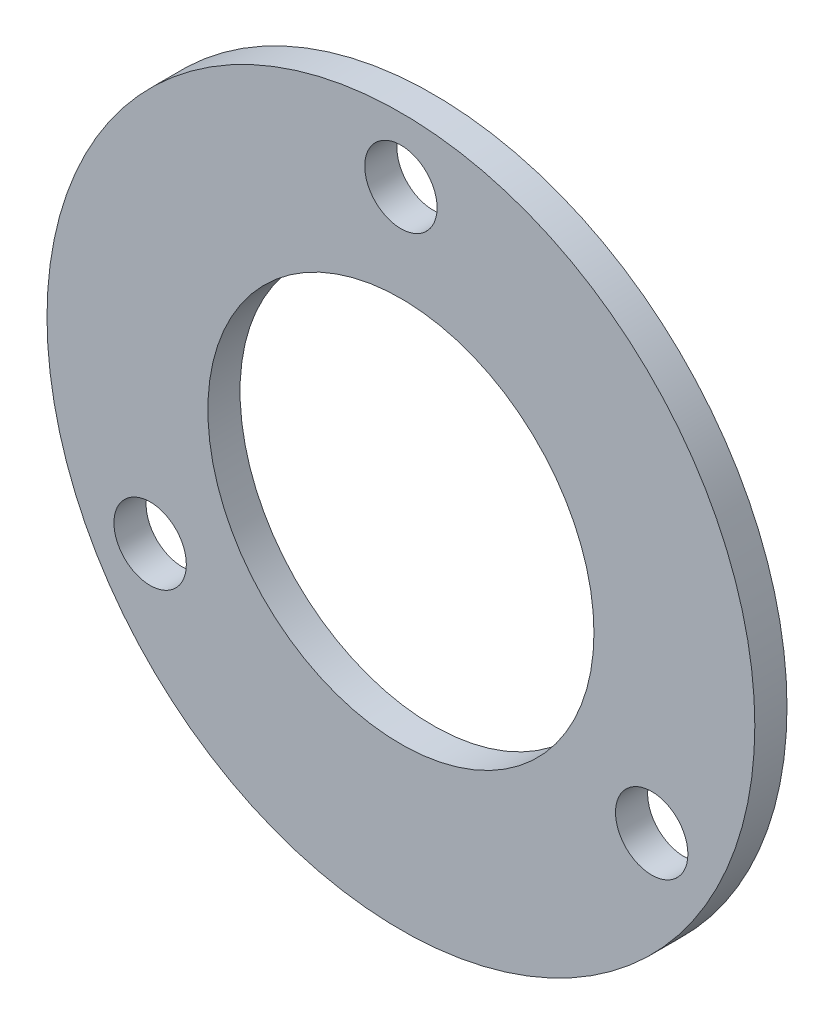
SolidWorks part; units mm, degrees
ref_plane "Front Plane" through (0, 0, 0) normal (0, 0, 1) x (1, 0, 0)
ref_plane "Top Plane" through (0, 0, 0) normal (0, 1, 0) x (1, 0, 0)
ref_plane "Right Plane" through (0, 0, 0) normal (1, 0, 0) x (0, 0, -1)
sketch "Sketch1" plane through (0, 0, 0) normal (0, 0, 1) x (1, 0, 0)
  circle A0 centre (0, 0) radius 12
  circle A1 centre (0, 0) radius 22
  dimension "D1" = 44
  dimension "D2" = 24
extrude "Boss-Extrude1" add sketch "Sketch1" along normal mid plane 2
sketch "Sketch2" plane through (0, 0, 1) normal (0, 0, 1) x (1, 0, 0)
  circle A0 centre (0, 0) radius 18
  circle A1 centre (0, 18) radius 2.25
  circle A2 centre (15.5885, -9) radius 2.25
  circle A3 centre (-15.5885, -9) radius 2.25
  point P12 (0, 0)
  dimension "D1" = 36
  dimension "D2" = 4.5
  dimension "D3" = 3
extrude "Cut-Extrude1" cut sketch "Sketch2" against normal through all both contours A0 A1 | A3 | A2
